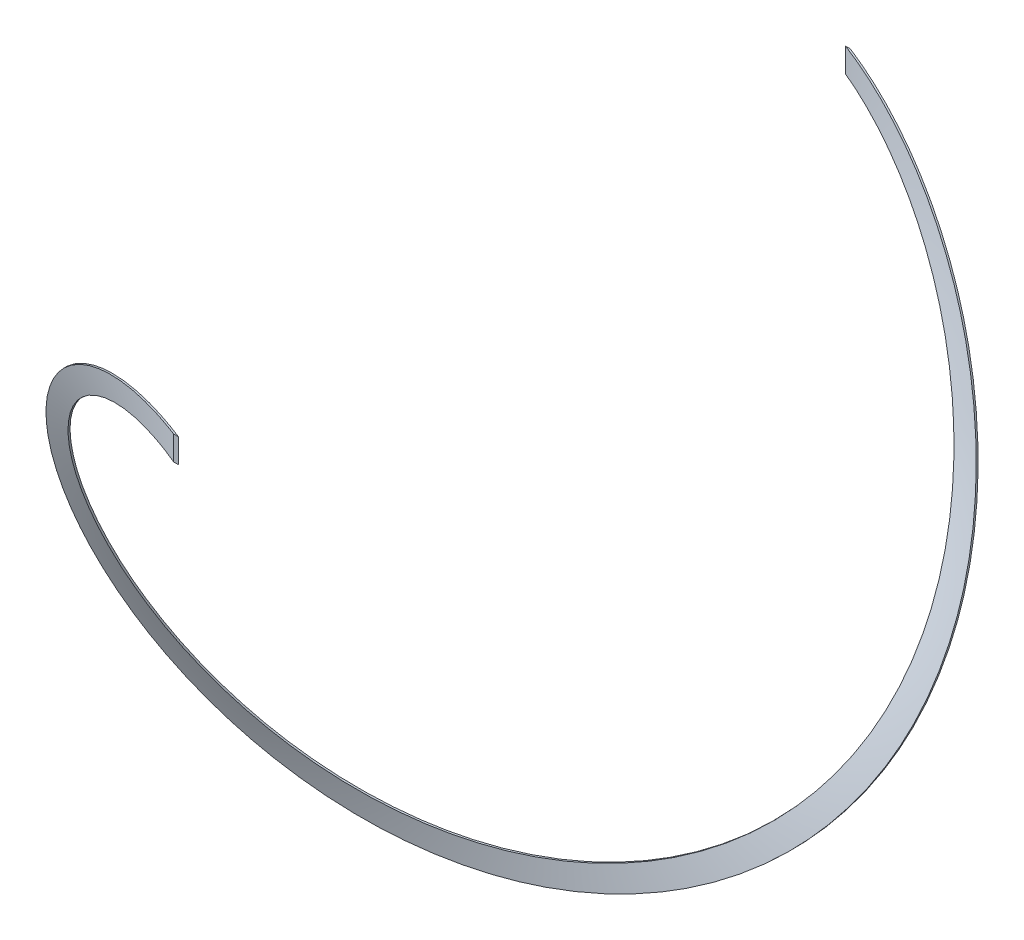
SolidWorks part; units mm, degrees
ref_plane "Front Plane" through (0, 0, 0) normal (0, 0, 1) x (1, 0, 0)
ref_plane "Top Plane" through (0, 0, 0) normal (0, 1, 0) x (1, 0, 0)
ref_plane "Right Plane" through (0, 0, 0) normal (1, 0, 0) x (0, 0, -1)
sketch "Sketch1" plane through (0, 0, 0) normal (0, 0, 1) x (1, 0, 0)
  circle A0 centre (0, 0) radius 342.4
  dimension "D1" = 684.8
curve "Helix/Spiral1" pitch 833 height 833 turns 1
sketch "Sketch2" plane through (0, 0, 0) normal (0, 0, 1) x (1, 0, 0)
  line L0 (-3, 342.4) -> (3, 342.4)
  line L1 (3, 342.4) -> (3, 312.4)
  line L2 (3, 312.4) -> (-3, 312.4)
  line L3 (-3, 312.4) -> (-3, 342.4)
  dimension "D2" = 6
  dimension "D3" = 30
sweep "Sweep1" add profiles "Sketch2" path "Helix/Spiral1"
sketch "Sketch3" plane through (0, 0, 0) normal (0, 0, 1) x (1, 0, 0)
  line L0 (0, -202.7078) -> (0, 202.7078)
  circle A0 centre (0, 0) radius 202.7078
  point P6 (0, 0)
